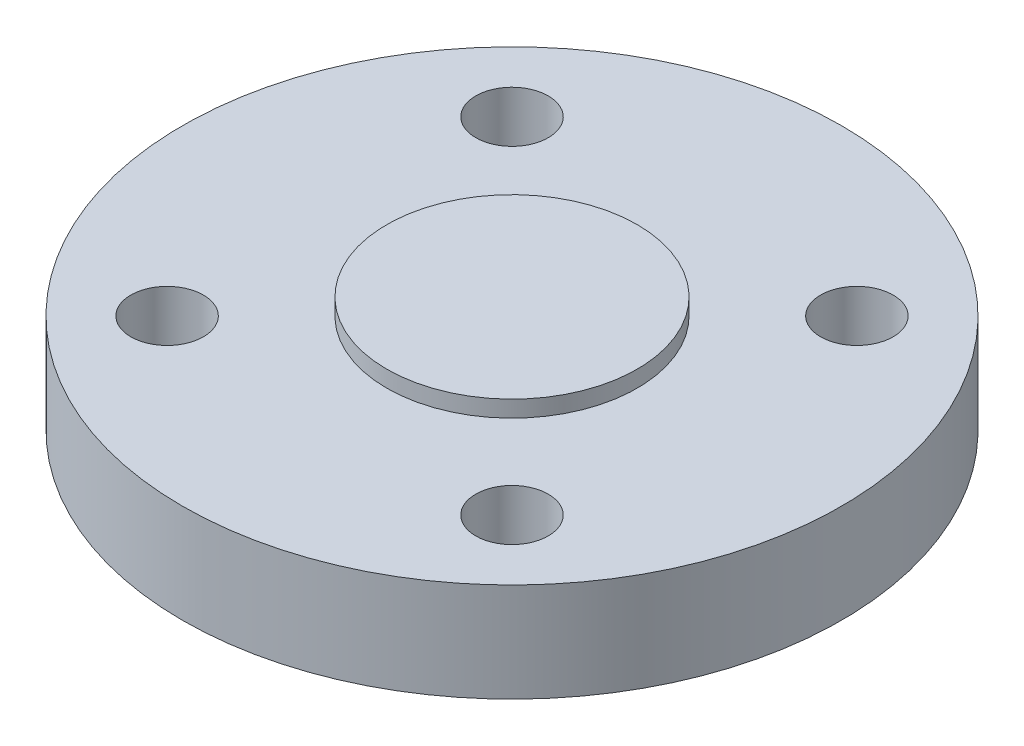
SolidWorks part; units mm, degrees
ref_plane "前视基准面" through (0, 0, 0) normal (0, 0, 1) x (1, 0, 0)
ref_plane "上视基准面" through (0, 0, 0) normal (0, 1, 0) x (1, 0, 0)
ref_plane "右视基准面" through (0, 0, 0) normal (1, 0, 0) x (0, 0, -1)
sketch "草图1" plane through (0, 0, 0) normal (0, 1, 0) x (1, 0, 0)
  circle A0 centre (0, 0) radius 50
  dimension "D1" = 100
extrude "凸台-拉伸1" add sketch "草图1" along normal blind 15
sketch "草图2" plane through (0, 15, 0) normal (0, 1, 0) x (1, 0, 0)
  circle A0 centre (0, 0) radius 19
  dimension "D1" = 38
extrude "凸台-拉伸2" add sketch "草图2" along normal blind 2.5
sketch "草图3" plane through (0, 15, 0) normal (0, 1, 0) x (1, 0, 0)
  line L0 (37, 0) -> (0, 0)
  line L1 (0, 0) -> (26.163, 26.163)
  circle A0 centre (0, 0) radius 37 construction
  circle A1 centre (26.163, 26.163) radius 5.5
  circle A2 centre (0, 0) radius 37 construction
  circle A3 centre (26.163, -26.163) radius 5.5
  circle A4 centre (0, 0) radius 37 construction
  circle A5 centre (-26.163, -26.163) radius 5.5
  circle A6 centre (0, 0) radius 37 construction
  circle A7 centre (-26.163, 26.163) radius 5.5
  dimension "D1" = 74
  dimension "D3" = 11
  dimension "D2" = 45
  dimension "D4" = 4
extrude "切除-拉伸1" cut sketch "草图3" against normal through all both and the other way through all
